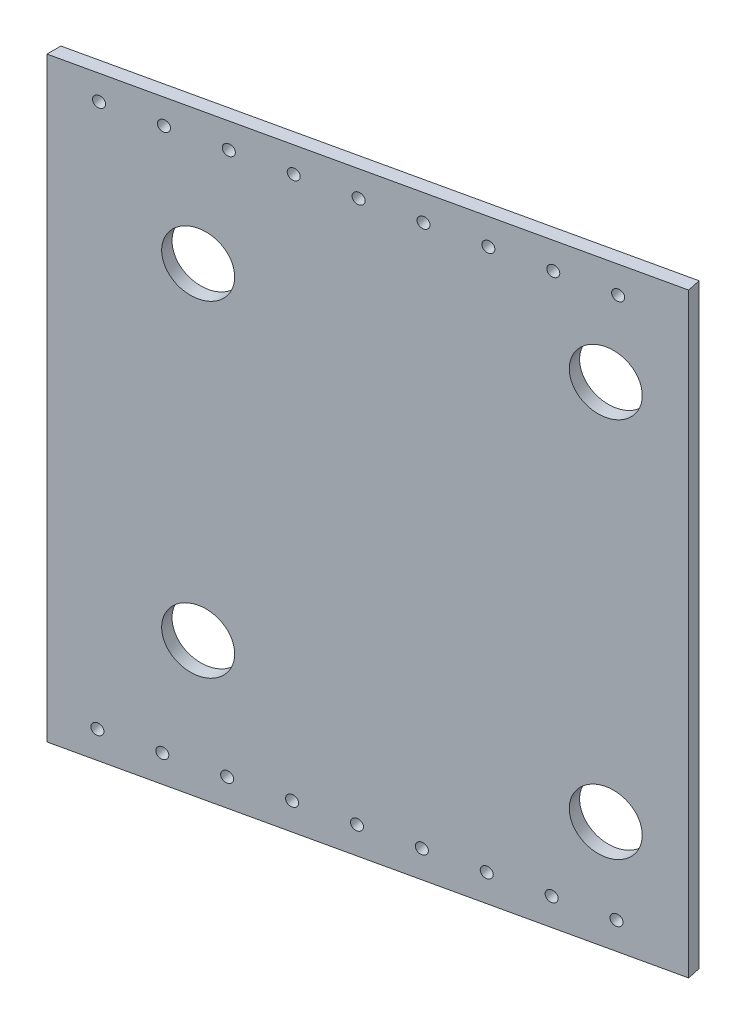
SolidWorks part; units mm, degrees
ref_plane "Front Plane" through (0, 0, 0) normal (0, 0, 1) x (1, 0, 0)
ref_plane "Top Plane" through (0, 0, 0) normal (0, 1, 0) x (1, 0, 0)
ref_plane "Right Plane" through (0, 0, 0) normal (1, 0, 0) x (0, 0, -1)
ref_plane "Plane1" through (191.2542, 0, 862.6918) normal (0.2164, 0, 0.9763) x (0, 1, 0)
sketch "Sketch1" plane through (191.2542, 0, 862.6918) normal (0.2164, 0, 0.9763) x (0, 1, 0)
  line L0 (6.35, -540.635) -> (284.48, -540.635)
  line L1 (284.48, -540.635) -> (284.48, -289.4438)
  line L2 (284.48, -289.4438) -> (6.35, -289.4438)
  line L3 (6.35, -289.4438) -> (6.35, -540.635)
extrude "Boss-Extrude1" add sketch "Sketch1" against normal blind 6.35
draft "Draft1" type of draft neutral plane draft angle 12.5 faces to draft 1 face at (473.1498, 145.415, 796.945) neutral plane through (191.2542, 0, 862.6918) neutral plane normal (0.2164, 0, 0.9763) reverse direction yes parameters "D1"=12.5
hole_wizard "Hole1" positions "Sketch3" profile "Sketch2" legacy
sketch "Sketch3" plane through (191.2542, 0, 862.6918) normal (0.2164, 0, 0.9763) x (0.9763, 0, -0.2164)
  point P0 (348.6301, 222.25)
  point P1 (508.1661, 234.95)
  point P2 (508.1661, 57.15)
  point P3 (348.6301, 69.85)
sketch "Sketch2" plane through (531.6203, 222.25, 787.2345) normal (0, 1, 0) x (0.9763, 0, -0.2164)
  line L0 (0, 0) -> (0, 59.1315)
  line L1 (0, 59.1315) -> (14.2875, 59.1315)
  line L2 (14.2875, 59.1315) -> (14.2875, 0)
  line L3 (14.2875, 0) -> (0, 0)
  line L4 (0, 110) -> (0, -10) construction
  dimension "Diameter" = 28.575
  dimension "Depth" = 59.1315
hole_wizard "#7 (0.201) Diameter Hole1" positions "Sketch5" profile "Sketch4" hole size "#7" standard "ANSI Inch"
sketch "Sketch5" plane through (191.2542, 0, 862.6918) normal (0.2164, 0, 0.9763) x (0.9763, 0, -0.2164)
  point P0 (360.6238, 272.6917)
  point P1 (411.4232, 272.4349)
  point P2 (462.2225, 272.1781)
  point P3 (513.0219, 271.9212)
  point P4 (487.6222, 272.0496)
  point P5 (436.8228, 272.3065)
  point P6 (386.0235, 272.5633)
  point P7 (335.2241, 272.8202)
  point P8 (512.3826, 19.05)
  point P9 (486.9826, 19.05)
  point P10 (461.5826, 19.05)
  point P11 (436.1826, 19.05)
  point P12 (410.7826, 19.05)
  point P13 (385.3826, 19.05)
  point P14 (359.9826, 19.05)
  point P15 (334.5826, 19.05)
  point P16 (309.1826, 19.05)
  point P17 (309.8245, 272.9486)
sketch "Sketch4" plane through (543.3298, 272.6917, 784.6385) normal (0, 1, 0) x (0.9763, 0, -0.2164)
  line L0 (0, 0) -> (0, 59.1315)
  line L1 (0, 59.1315) -> (2.5527, 59.1315)
  line L2 (2.5527, 59.1315) -> (2.5527, 0)
  line L5 (2.5527, 0) -> (0, 0)
  line L11 (0, -6.35) -> (0, 107.95) construction
  dimension "Thru Hole Dia." = 5.1054
  dimension "Thru Hole Depth" = 59.1315
